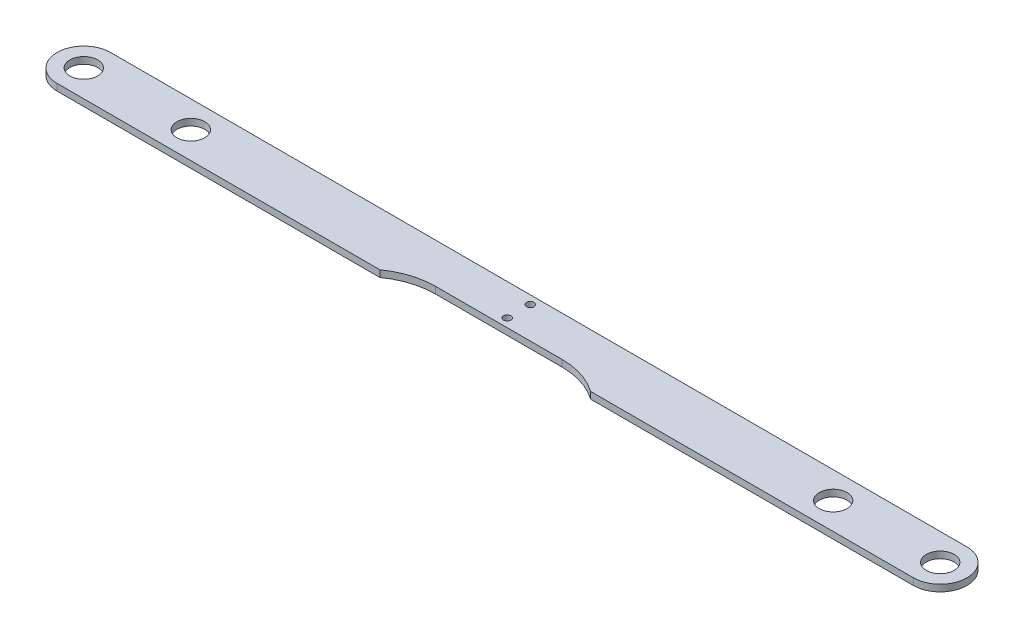
SolidWorks part; units mm, degrees
ref_plane "Front Plane" through (0, 0, 0) normal (0, 0, 1) x (1, 0, 0)
ref_plane "Top Plane" through (0, 0, 0) normal (0, 1, 0) x (1, 0, 0)
ref_plane "Right Plane" through (0, 0, 0) normal (1, 0, 0) x (0, 0, -1)
sketch "Sketch5" plane through (0, 0, 0) normal (0, 1, 0) x (1, 0, 0)
  line L0 (0, 2.75) -> (0, -2.75) construction
  line L1 (101.6, 4.75) -> (-101.6, 4.75)
  line L2 (-101.6, -7.95) -> (-101.6, 4.75) construction
  line L3 (0, 4.75) -> (0, -4.75) construction
  line L4 (-101.6, -1.6) -> (101.6, -1.6) construction
  line L5 (101.6, 4.75) -> (101.6, -7.95) construction
  line L6 (-15, -4.75) -> (-15, -21.975) construction
  line L7 (15, -4.75) -> (15, -21.975) construction
  line L15 (-101.6, -7.95) -> (-25, -7.95)
  line L21 (-15, -4.75) -> (15, -4.75)
  line L26 (25, -7.95) -> (101.6, -7.95)
  circle A0 centre (-101.6, -1.6) radius 3.302
  circle A1 centre (0, 2.75) radius 0.889
  circle A2 centre (101.6, -1.6) radius 3.302
  circle A3 centre (0, -2.75) radius 0.889
  arc A4 (-101.6, 4.75) -> (-101.6, -7.95) centre (-101.6, -1.6) ccw
  arc A5 (101.6, 4.75) -> (101.6, -7.95) centre (101.6, -1.6) cw
  arc A7 (15, -4.75) -> (25, -7.95) centre (15, -21.975) cw
  arc A8 (-15, -4.75) -> (-25, -7.95) centre (-15, -21.975) ccw
  circle A9 centre (-76.2, -1.6) radius 3.302
  circle A10 centre (76.2, -1.6) radius 3.302
  point P11 (0, 0)
  dimension "D2" = 1.778
  dimension "D3" = 1.778
  dimension "D12" = 6.604
  dimension "D13" = 25.4
  dimension "D4" = 9.5
  dimension "D5" = 30
  dimension "D6" = 12.7
  dimension "D7" = 5.5
  dimension "D8" = 10
  dimension "D9" = 10
  dimension "D10" = 203.2
  dimension "D11" = 203.2
  dimension "D14" = 25.4
extrude "Boss-Extrude1" add sketch "Sketch5" along normal blind 1.5875
